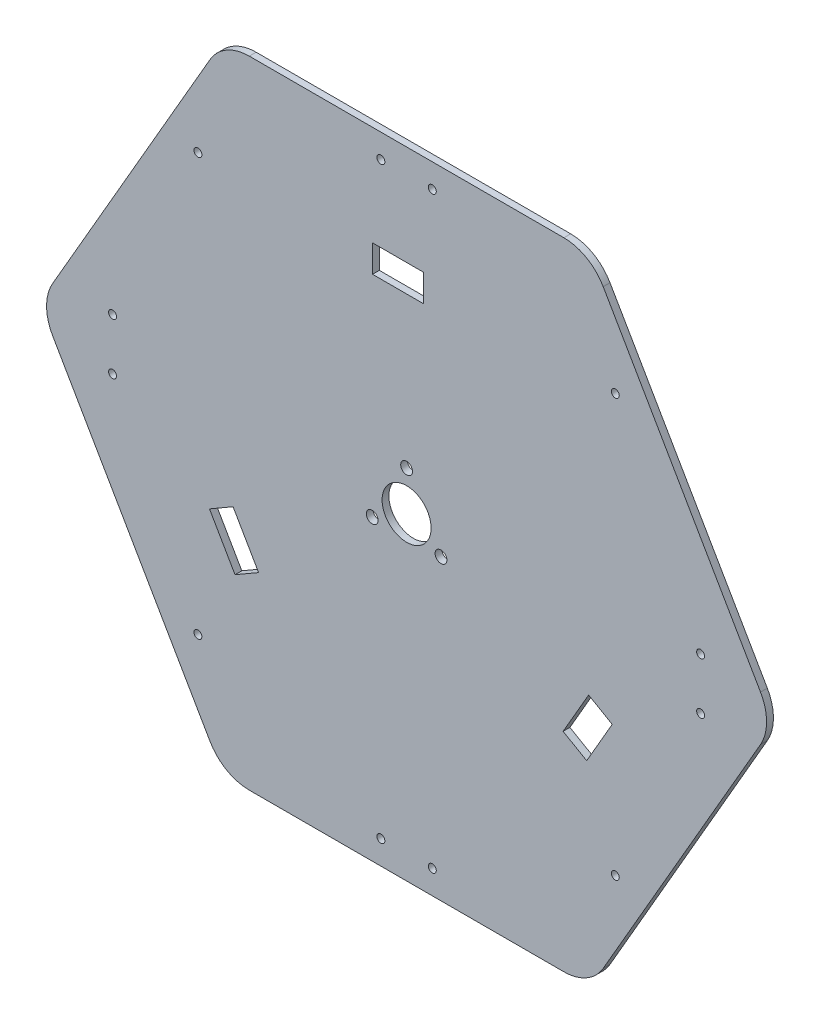
SolidWorks part; units mm, degrees
ref_plane "Alzado" through (0, 0, 0) normal (0, 0, 1) x (1, 0, 0)
ref_plane "Planta" through (0, 0, 0) normal (0, 1, 0) x (1, 0, 0)
ref_plane "Vista lateral" through (0, 0, 0) normal (1, 0, 0) x (0, 0, -1)
sketch "Croquis1" plane through (0, 0, 0) normal (0, 0, 1) x (1, 0, 0)
  line L0 (7.5, 95.9218) -> (-15, 83.9218) construction
  line L1 (-15, 95.9218) -> (7.5, 95.9218)
  line L2 (-15, 95.9218) -> (-15, 83.9218)
  line L3 (-15, 83.9218) -> (7.5, 83.9218)
  line L4 (7.5, 95.9218) -> (7.5, 83.9218)
  line L5 (-15, 95.9218) -> (7.5, 83.9218) construction
  line L6 (90.5708, -34.9705) -> (80.1784, -28.9705)
  line L7 (90.5708, -34.9705) -> (79.3208, -54.4561)
  line L8 (79.3208, -54.4561) -> (68.9284, -48.4561)
  line L9 (80.1784, -28.9705) -> (68.9284, -48.4561)
  line L10 (-75.5708, -60.9513) -> (-65.1784, -54.9513)
  line L11 (-75.5708, -60.9513) -> (-86.8208, -41.4657)
  line L12 (-86.8208, -41.4657) -> (-76.4284, -35.4657)
  line L13 (-65.1784, -54.9513) -> (-76.4284, -35.4657)
  line L14 (0, -0.7536) -> (0, 0) construction
  line L15 (0, 0) -> (0, 17.5) construction
  line L17 (-80.829, -140) -> (80.829, -140)
  line L18 (80.829, -140) -> (161.6581, 0)
  line L19 (161.6581, 0) -> (80.829, 140)
  line L20 (80.829, 140) -> (-80.829, 140)
  line L21 (-80.829, 140) -> (-161.6581, 0)
  line L22 (-161.6581, 0) -> (-80.829, -140)
  circle A0 centre (0, 0) radius 150
  circle A1 centre (0, 0) radius 10.8
  circle A2 centre (0, 0) radius 90 construction
  circle A3 centre (-3.75, 89.9218) radius 40 construction
  circle A4 centre (79.7496, -41.7133) radius 40 construction
  circle A5 centre (-75.9996, -48.2085) radius 40 construction
  circle A6 centre (0, 0) radius 17.5 construction
  circle A7 centre (0, 17.5) radius 2.6
  circle A8 centre (0, 0) radius 140 construction
  circle A9 centre (15.1554, -8.75) radius 2.6
  circle A10 centre (-15.1554, -8.75) radius 2.6
  point P11 (-3.75, 89.9218)
  point P18 (0, 0)
  point P28 (0, 0)
  point P39 (0, 0)
  point P46 (0, 140)
  dimension "D1" = 300
  dimension "D2" = 21.6
  dimension "D3" = 180
  dimension "D4" = 80
  dimension "D9" = 5.2
  dimension "D10" = 3
  dimension "D11" = 50
  dimension "D5" = 12
  dimension "D6" = 22.5
  dimension "D12" = 3.75
  dimension "D7" = 3
  dimension "D8" = 3
extrude "Saliente-Extruir1" add sketch "Croquis1" along normal blind 3 contours L19 A0 L20 L21 L22 L17 L18 A10 A9 A7 A1 L1 L4 L3 L2 L9 L6 L7 L8 L13 L10 L11 L12 | A0 L20 L21 | A0 L19 L20 | A0 L18 L19 | A0 L17 L18 | A0 L22 L17 | A0 L21 L22
fillet "Redondeo1" radius 20 6 edges at (80.829, 140, 1.5) (-80.829, 140, 1.5) (-161.6581, 0, 1.5) (-80.829, -140, 1.5) (80.829, -140, 1.5) (161.6581, 0, 1.5)
sketch "Croquis2" plane through (0, 0, 0) normal (0, 0, -1) x (-1, 0, 0)
  circle A0 centre (0, 0) radius 102.5 construction
  circle A1 centre (0, 0) radius 140 construction
  dimension "D1" = 280
  dimension "D2" = 205
sketch "Croquis3" plane through (0, 0, 0) normal (0, 0, -1) x (1, 0, 0)
  circle A0 centre (129.5053, 11.3302) radius 1.75
  circle A1 centre (91.9239, 91.9239) radius 1.75
  circle A2 centre (11.3302, 129.5053) radius 1.75
extrude "Cortar-Extruir1" cut sketch "Croquis3" against normal through all
pattern_circular "MatrizC1" count 4 over 360 about axis through (0, 0, 0) along (0, 0, 1) of "Cortar-Extruir1"
